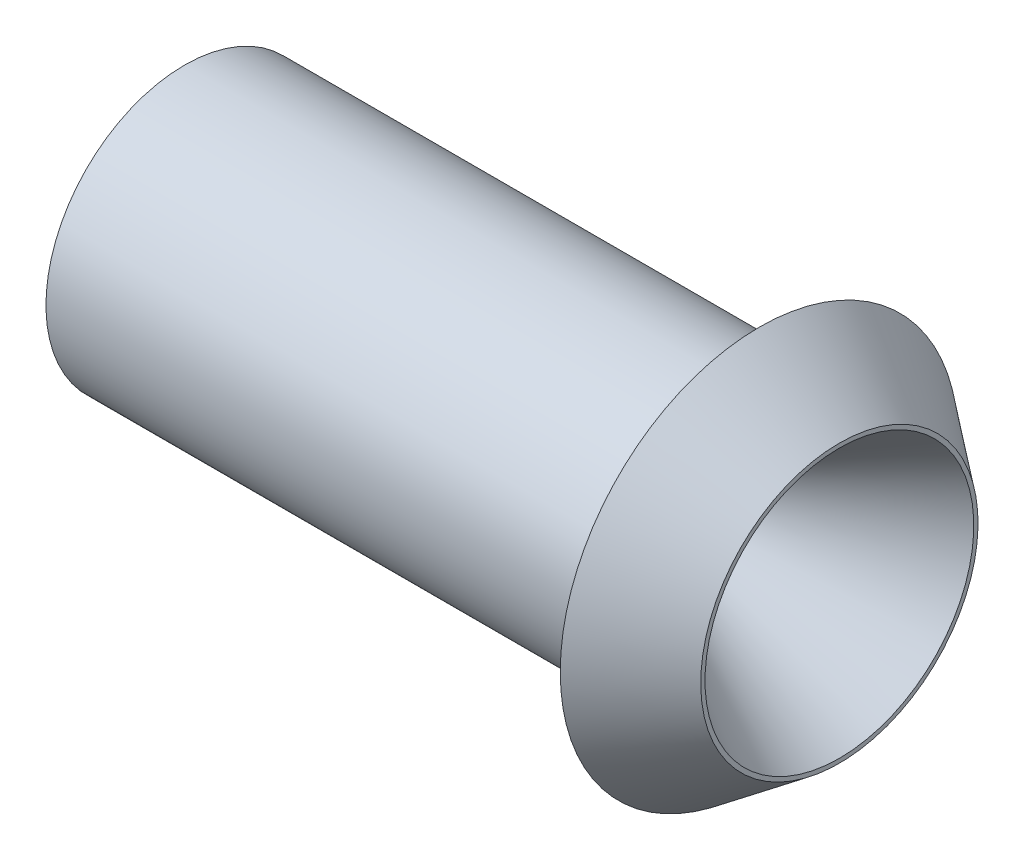
SolidWorks part; units mm, degrees
material "AISI 316 Annealed Stainless Steel Bar (SS)"
ref_plane "Front Plane" through (0, 0, 0) normal (0, 0, 1) x (1, 0, 0)
ref_plane "Top Plane" through (0, 0, 0) normal (0, 1, 0) x (1, 0, 0)
ref_plane "Right Plane" through (0, 0, 0) normal (1, 0, 0) x (0, 0, -1)
sketch "Sketch1" plane through (0, 0, 0) normal (0, 0, 1) x (1, 0, 0)
  line L0 (0, 0) -> (0, 8.255)
  line L1 (0, 8.255) -> (34.2128, 8.255)
  line L2 (34.2128, 8.255) -> (34.2128, 11.8491)
  line L3 (34.2128, 11.8491) -> (38.9824, 8.255)
  line L4 (38.9824, 8.255) -> (38.9824, 0)
  line L5 (38.9824, 0) -> (0, 0) construction
  line L7 (38.9824, 8.001) -> (30.1593, 2.907)
  line L8 (30.1593, 2.907) -> (28.8893, 2.907)
  line L9 (28.8893, 2.907) -> (0, 8.001)
  line L10 (0, 4.7625) -> (18.3664, 4.7625) construction
  line L11 (0, 3.175) -> (27.3696, 3.175) construction
  dimension "D1" = 16.51
  dimension "D2" = 34.2128
  dimension "D3" = 23.6982
  dimension "D4" = 37
  dimension "D5" = 0.254
  dimension "D6" = 0.254
  dimension "D7" = 30
  dimension "D8" = 28.8893
  dimension "ID" = 5.8141
  dimension "D9" = 1.27
  dimension "D10" = 10
  dimension "D11" = 3.175
  dimension "D12" = 4.7625
  dimension "D13" = 27.3696
  dimension "D14" = 18.3664
revolve "Revolve1" add sketch "Sketch1" angle 360 about L5
